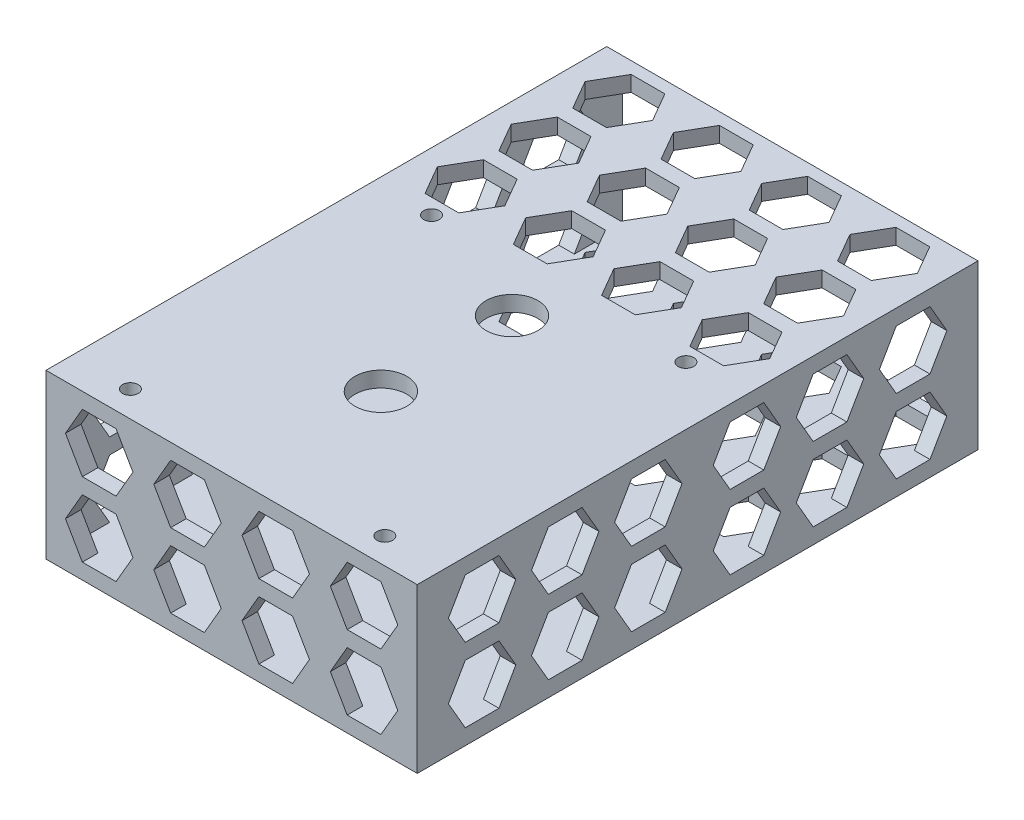
SolidWorks part; units mm, degrees
ref_plane "Front Plane" through (0, 0, 0) normal (0, 0, 1) x (1, 0, 0)
ref_plane "Top Plane" through (0, 0, 0) normal (0, 1, 0) x (1, 0, 0)
ref_plane "Right Plane" through (0, 0, 0) normal (1, 0, 0) x (0, 0, -1)
sketch "Sketch5" plane through (0, 0, 0) normal (0, 1, 0) x (1, 0, 0)
  line L1 (-35.75, -54) -> (35.75, -54)
  line L2 (-35.75, -54) -> (-35.75, 54)
  line L3 (-35.75, 54) -> (35.75, 54)
  line L4 (35.75, -54) -> (35.75, 54)
  line L5 (-35.75, -54) -> (35.75, 54) construction
  line L6 (-35.75, 54) -> (35.75, -54) construction
  point P0 (0, 0)
  dimension "D1" = 71.5
  dimension "D2" = 108
extrude "Boss-Extrude4" add sketch "Sketch5" along normal blind 31.5
shell "Shell1" thickness 3
sketch "Sketch7" plane through (0, 31.5, 0) normal (0, 1, 0) x (1, 0, 0)
  line L0 (-35.75, 0) -> (35.75, 0) construction
  line L1 (-35.75, 54) -> (-35.75, -54) construction
  line L2 (35.75, -54) -> (35.75, 54) construction
  circle A0 centre (0, 0) radius 1.75
  circle A2 centre (0, -25.25) radius 1.75
  dimension "D1" = 3.5
  dimension "D3" = 35.75
  dimension "D2" = 25.25
  dimension "D4" = 3.5
extrude "Cut-Extrude1" cut sketch "Sketch7" against normal through all
sketch "Sketch8" plane through (0, 31.5, 0) normal (0, 1, 0) x (1, 0, 0)
  circle A0 centre (0, -25.25) radius 5
  circle A1 centre (0, 0) radius 5
  circle A3 centre (0, 25.25) radius 5 [skipped]
  dimension "D1" = 10
  dimension "D3" = 25.25
  dimension "D2" = 3
extrude "Cut-Extrude2" cut sketch "Sketch8" against normal up to next
chamfer "Chamfer1" distance 1.5 angle 35 2 edges at (0, 3, 23.5) (0, 3, -1.75)
sketch "Sketch9" plane through (0, 31.5, 0) normal (0, 1, 0) x (1, 0, 0)
  line L0 (0, 54) -> (0, -54) construction
  line L1 (35.75, 54) -> (-35.75, 54) construction
  line L2 (-35.75, -54) -> (35.75, -54) construction
  circle A0 centre (-24.5, -49) radius 1.5
  circle A1 centre (24.5, -49) radius 1.5
  circle A2 centre (-24.5, 9) radius 1.5
  circle A3 centre (24.5, 9) radius 1.5
  dimension "D1" = 24.5
  dimension "D2" = 5
  dimension "D3" = 3
  dimension "D5" = 58
  dimension "D4" = 2
extrude "Cut-Extrude3" cut sketch "Sketch9" against normal up to next
sketch "Sketch10" plane through (0, 0, 54) normal (0, 0, 1) x (1, 0, 0)
  line L0 (-34, 28.5) -> (34, 28.5) construction
  line L1 (34, 28.5) -> (34, 3) construction
  line L2 (34, 3) -> (-34, 3) construction
  line L3 (-34, 3) -> (-34, 28.5) construction
  line L4 (-35.75, 31.5) -> (-35.75, 0) construction
  line L5 (-35.75, 31.5) -> (35.75, 31.5) construction
  line L6 (35.75, 31.5) -> (35.75, 0) construction
  line L7 (-35.75, 0) -> (35.75, 0) construction
  line L8 (-34, 15.75) -> (0, 15.75) construction
  line L9 (-32, 22.875) -> (-28.7524, 17.25)
  line L10 (-28.7524, 17.25) -> (-22.2572, 17.25)
  line L11 (-22.2572, 17.25) -> (-19.0096, 22.875)
  line L12 (-19.0096, 22.875) -> (-22.2572, 28.5)
  line L13 (-22.2572, 28.5) -> (-28.7524, 28.5)
  line L14 (-28.7524, 28.5) -> (-32, 22.875)
  line L15 (0, 28.5) -> (0, 3) construction
  line L16 (-28.7524, 3) -> (-32, 8.625)
  line L17 (-22.2572, 3) -> (-28.7524, 3)
  line L18 (-19.0096, 8.625) -> (-22.2572, 3)
  line L19 (-22.2572, 14.25) -> (-19.0096, 8.625)
  line L20 (-28.7524, 14.25) -> (-22.2572, 14.25)
  line L21 (-32, 8.625) -> (-28.7524, 14.25)
  line L22 (-17, 15.75) -> (-17, 28.5) construction
  line L23 (-11.7428, 3) -> (-5.2476, 3)
  line L24 (-14.9904, 8.625) -> (-11.7428, 3)
  line L25 (-11.7428, 14.25) -> (-14.9904, 8.625)
  line L26 (-5.2476, 14.25) -> (-11.7428, 14.25)
  line L27 (-2, 8.625) -> (-5.2476, 14.25)
  line L28 (-5.2476, 3) -> (-2, 8.625)
  line L29 (-5.2476, 28.5) -> (-2, 22.875)
  line L30 (-11.7428, 28.5) -> (-5.2476, 28.5)
  line L31 (-14.9904, 22.875) -> (-11.7428, 28.5)
  line L32 (-11.7428, 17.25) -> (-14.9904, 22.875)
  line L33 (-5.2476, 17.25) -> (-11.7428, 17.25)
  line L34 (-2, 22.875) -> (-5.2476, 17.25)
  line L35 (22.2572, 3) -> (28.7524, 3)
  line L36 (19.0096, 8.625) -> (22.2572, 3)
  line L37 (22.2572, 14.25) -> (19.0096, 8.625)
  line L38 (28.7524, 14.25) -> (22.2572, 14.25)
  line L39 (32, 8.625) -> (28.7524, 14.25)
  line L40 (28.7524, 3) -> (32, 8.625)
  line L41 (14.9904, 8.625) -> (11.7428, 3)
  line L42 (11.7428, 14.25) -> (14.9904, 8.625)
  line L43 (5.2476, 14.25) -> (11.7428, 14.25)
  line L44 (2, 8.625) -> (5.2476, 14.25)
  line L45 (5.2476, 3) -> (2, 8.625)
  line L46 (11.7428, 3) -> (5.2476, 3)
  line L47 (11.7428, 28.5) -> (5.2476, 28.5)
  line L48 (14.9904, 22.875) -> (11.7428, 28.5)
  line L49 (11.7428, 17.25) -> (14.9904, 22.875)
  line L50 (5.2476, 17.25) -> (11.7428, 17.25)
  line L51 (2, 22.875) -> (5.2476, 17.25)
  line L52 (5.2476, 28.5) -> (2, 22.875)
  line L53 (28.7524, 28.5) -> (32, 22.875)
  line L54 (22.2572, 28.5) -> (28.7524, 28.5)
  line L55 (19.0096, 22.875) -> (22.2572, 28.5)
  line L56 (22.2572, 17.25) -> (19.0096, 22.875)
  line L57 (28.7524, 17.25) -> (22.2572, 17.25)
  line L58 (32, 22.875) -> (28.7524, 17.25)
  circle A0 centre (-25.5048, 22.875) radius 5.625 construction
  dimension "D5" = 1.5
  dimension "D1" = 1.75
  dimension "D2" = 3
  dimension "D3" = 1.75
  dimension "D4" = 3
  dimension "D6" = 2
extrude "Cut-Extrude4" cut sketch "Sketch10" against normal up to next
sketch "Sketch12" plane through (-35.75, 0, 0) normal (-1, 0, 0) x (0, 0, 1)
  line L0 (51, 28.5) -> (-51, 28.5) construction
  line L1 (-51, 28.5) -> (-51, 3) construction
  line L2 (-51, 3) -> (51, 3) construction
  line L3 (51, 3) -> (51, 28.5) construction
  line L4 (-54, 31.5) -> (54, 31.5) construction
  line L5 (-54, 0) -> (54, 0) construction
  line L6 (-54, 31.5) -> (-54, 0) construction
  line L7 (54, 31.5) -> (54, 0) construction
  line L8 (0, 15.75) -> (51, 15.75) construction
  line L9 (0, 28.5) -> (0, 3) construction
  line L10 (25.5, 15.75) -> (25.5, 28.5) construction
  line L11 (48, 22.875) -> (44.7524, 28.5)
  line L12 (44.7524, 28.5) -> (38.2572, 28.5)
  line L13 (38.2572, 28.5) -> (35.0096, 22.875)
  line L14 (35.0096, 22.875) -> (38.2572, 17.25)
  line L15 (38.2572, 17.25) -> (44.7524, 17.25)
  line L16 (44.7524, 17.25) -> (48, 22.875)
  line L17 (6.2476, 17.25) -> (3, 22.875)
  line L18 (31.9952, 22.875) -> (28.7476, 28.5)
  line L19 (28.7476, 28.5) -> (22.2524, 28.5)
  line L20 (22.2524, 28.5) -> (19.0048, 22.875)
  line L21 (19.0048, 22.875) -> (22.2524, 17.25)
  line L22 (22.2524, 17.25) -> (28.7476, 17.25)
  line L23 (28.7476, 17.25) -> (31.9952, 22.875)
  line L24 (12.7428, 17.25) -> (6.2476, 17.25)
  line L25 (15.9904, 22.875) -> (12.7428, 17.25)
  line L26 (12.7428, 28.5) -> (15.9904, 22.875)
  line L27 (6.2476, 28.5) -> (12.7428, 28.5)
  line L28 (3, 22.875) -> (6.2476, 28.5)
  line L29 (44.7524, 14.25) -> (48, 8.625)
  line L30 (38.2572, 14.25) -> (44.7524, 14.25)
  line L31 (35.0096, 8.625) -> (38.2572, 14.25)
  line L32 (38.2572, 3) -> (35.0096, 8.625)
  line L33 (44.7524, 3) -> (38.2572, 3)
  line L34 (48, 8.625) -> (44.7524, 3)
  line L35 (28.7476, 14.25) -> (31.9952, 8.625)
  line L36 (22.2524, 14.25) -> (28.7476, 14.25)
  line L37 (19.0048, 8.625) -> (22.2524, 14.25)
  line L38 (22.2524, 3) -> (19.0048, 8.625)
  line L39 (28.7476, 3) -> (22.2524, 3)
  line L40 (31.9952, 8.625) -> (28.7476, 3)
  line L41 (12.7428, 14.25) -> (6.2476, 14.25)
  line L42 (15.9904, 8.625) -> (12.7428, 14.25)
  line L43 (12.7428, 3) -> (15.9904, 8.625)
  line L44 (6.2476, 3) -> (12.7428, 3)
  line L45 (3, 8.625) -> (6.2476, 3)
  line L46 (6.2476, 14.25) -> (3, 8.625)
  line L47 (-15.9904, 8.625) -> (-12.7428, 14.25)
  line L48 (-12.7428, 3) -> (-15.9904, 8.625)
  line L49 (-6.2476, 3) -> (-12.7428, 3)
  line L50 (-3, 8.625) -> (-6.2476, 3)
  line L51 (-6.2476, 14.25) -> (-3, 8.625)
  line L52 (-12.7428, 14.25) -> (-6.2476, 14.25)
  line L53 (-22.2524, 14.25) -> (-28.7476, 14.25)
  line L54 (-19.0048, 8.625) -> (-22.2524, 14.25)
  line L55 (-22.2524, 3) -> (-19.0048, 8.625)
  line L56 (-28.7476, 3) -> (-22.2524, 3)
  line L57 (-31.9952, 8.625) -> (-28.7476, 3)
  line L58 (-28.7476, 14.25) -> (-31.9952, 8.625)
  line L59 (-38.2572, 14.25) -> (-44.7524, 14.25)
  line L60 (-35.0096, 8.625) -> (-38.2572, 14.25)
  line L61 (-38.2572, 3) -> (-35.0096, 8.625)
  line L62 (-44.7524, 3) -> (-38.2572, 3)
  line L63 (-48, 8.625) -> (-44.7524, 3)
  line L64 (-44.7524, 14.25) -> (-48, 8.625)
  line L65 (-44.7524, 17.25) -> (-48, 22.875)
  line L66 (-38.2572, 17.25) -> (-44.7524, 17.25)
  line L67 (-35.0096, 22.875) -> (-38.2572, 17.25)
  line L68 (-38.2572, 28.5) -> (-35.0096, 22.875)
  line L69 (-44.7524, 28.5) -> (-38.2572, 28.5)
  line L70 (-48, 22.875) -> (-44.7524, 28.5)
  line L71 (-28.7476, 17.25) -> (-31.9952, 22.875)
  line L72 (-22.2524, 17.25) -> (-28.7476, 17.25)
  line L73 (-19.0048, 22.875) -> (-22.2524, 17.25)
  line L74 (-22.2524, 28.5) -> (-19.0048, 22.875)
  line L75 (-28.7476, 28.5) -> (-22.2524, 28.5)
  line L76 (-31.9952, 22.875) -> (-28.7476, 28.5)
  line L77 (-12.7428, 17.25) -> (-6.2476, 17.25)
  line L78 (-15.9904, 22.875) -> (-12.7428, 17.25)
  line L79 (-12.7428, 28.5) -> (-15.9904, 22.875)
  line L80 (-6.2476, 28.5) -> (-12.7428, 28.5)
  line L81 (-3, 22.875) -> (-6.2476, 28.5)
  line L82 (-6.2476, 17.25) -> (-3, 22.875)
  circle A0 centre (41.5048, 22.875) radius 5.625 construction
  circle A1 centre (25.5, 22.875) radius 5.625 construction
  dimension "D5" = 11.25
  dimension "D7" = 11.25
  dimension "D1" = 3
  dimension "D2" = 3
  dimension "D3" = 3
  dimension "D4" = 3
  dimension "D6" = 1.5
  dimension "D8" = 1.5
  dimension "D9" = 3
extrude "Cut-Extrude5" cut sketch "Sketch12" against normal through all
sketch "Sketch13" plane through (0, 31.5, 0) normal (0, 1, 0) x (1, 0, 0)
  line L0 (-34, 51.7) -> (34, 51.7) construction
  line L1 (34, 51.7) -> (34, 12) construction
  line L2 (34, 12) -> (-34, 12) construction
  line L3 (-34, 12) -> (-34, 51.7) construction
  line L5 (35.75, 54) -> (-35.75, 54) construction
  line L6 (-35.75, 54) -> (-35.75, -54) construction
  line L7 (35.75, -54) -> (35.75, 54) construction
  line L20 (0, 51.7) -> (0, 12) construction
  line L21 (0, 31.85) -> (-34, 31.85) construction
  line L22 (-17, 31.85) -> (-17, 12) construction
  line L23 (-22.2572, 51.7) -> (-19.0096, 46.075)
  line L24 (-19.0096, 31.85) -> (-22.2572, 37.475)
  line L25 (-22.2572, 37.475) -> (-28.7524, 37.475)
  line L26 (-28.7524, 37.475) -> (-32, 31.85)
  line L27 (-32, 31.85) -> (-28.7524, 26.225)
  line L28 (-28.7524, 26.225) -> (-22.2572, 26.225)
  line L29 (-22.2572, 26.225) -> (-19.0096, 31.85)
  line L30 (-19.0096, 17.625) -> (-22.2572, 23.25)
  line L31 (-22.2572, 23.25) -> (-28.7524, 23.25)
  line L32 (-28.7524, 23.25) -> (-32, 17.625)
  line L33 (-32, 17.625) -> (-28.7524, 12)
  line L34 (-28.7524, 12) -> (-22.2572, 12)
  line L35 (-22.2572, 12) -> (-19.0096, 17.625)
  line L36 (-28.7524, 51.7) -> (-22.2572, 51.7)
  line L37 (-32, 46.075) -> (-28.7524, 51.7)
  line L38 (-28.7524, 40.45) -> (-32, 46.075)
  line L39 (-22.2572, 40.45) -> (-28.7524, 40.45)
  line L40 (-19.0096, 46.075) -> (-22.2572, 40.45)
  line L41 (-5.2476, 51.7) -> (-11.7428, 51.7)
  line L42 (-2, 46.075) -> (-5.2476, 51.7)
  line L43 (-5.2476, 40.45) -> (-2, 46.075)
  line L44 (-11.7428, 40.45) -> (-5.2476, 40.45)
  line L45 (-14.9904, 46.075) -> (-11.7428, 40.45)
  line L46 (-11.7428, 51.7) -> (-14.9904, 46.075)
  line L47 (-11.7428, 26.225) -> (-14.9904, 31.85)
  line L48 (-5.2476, 26.225) -> (-11.7428, 26.225)
  line L49 (-2, 31.85) -> (-5.2476, 26.225)
  line L50 (-5.2476, 37.475) -> (-2, 31.85)
  line L51 (-11.7428, 37.475) -> (-5.2476, 37.475)
  line L52 (-14.9904, 31.85) -> (-11.7428, 37.475)
  line L53 (-11.7428, 12) -> (-14.9904, 17.625)
  line L54 (-5.2476, 12) -> (-11.7428, 12)
  line L55 (-2, 17.625) -> (-5.2476, 12)
  line L56 (-5.2476, 23.25) -> (-2, 17.625)
  line L57 (-11.7428, 23.25) -> (-5.2476, 23.25)
  line L58 (-14.9904, 17.625) -> (-11.7428, 23.25)
  line L59 (5.2476, 12) -> (11.7428, 12)
  line L60 (2, 17.625) -> (5.2476, 12)
  line L61 (5.2476, 23.25) -> (2, 17.625)
  line L62 (11.7428, 23.25) -> (5.2476, 23.25)
  line L63 (14.9904, 17.625) -> (11.7428, 23.25)
  line L64 (11.7428, 12) -> (14.9904, 17.625)
  line L65 (22.2572, 12) -> (19.0096, 17.625)
  line L66 (28.7524, 12) -> (22.2572, 12)
  line L67 (32, 17.625) -> (28.7524, 12)
  line L68 (28.7524, 23.25) -> (32, 17.625)
  line L69 (22.2572, 23.25) -> (28.7524, 23.25)
  line L70 (19.0096, 17.625) -> (22.2572, 23.25)
  line L71 (5.2476, 26.225) -> (11.7428, 26.225)
  line L72 (2, 31.85) -> (5.2476, 26.225)
  line L73 (5.2476, 37.475) -> (2, 31.85)
  line L74 (11.7428, 37.475) -> (5.2476, 37.475)
  line L75 (14.9904, 31.85) -> (11.7428, 37.475)
  line L76 (11.7428, 26.225) -> (14.9904, 31.85)
  line L77 (22.2572, 26.225) -> (19.0096, 31.85)
  line L78 (28.7524, 26.225) -> (22.2572, 26.225)
  line L79 (32, 31.85) -> (28.7524, 26.225)
  line L80 (28.7524, 37.475) -> (32, 31.85)
  line L81 (22.2572, 37.475) -> (28.7524, 37.475)
  line L82 (19.0096, 31.85) -> (22.2572, 37.475)
  line L83 (2, 46.075) -> (5.2476, 51.7)
  line L84 (5.2476, 40.45) -> (2, 46.075)
  line L85 (11.7428, 40.45) -> (5.2476, 40.45)
  line L86 (14.9904, 46.075) -> (11.7428, 40.45)
  line L87 (11.7428, 51.7) -> (14.9904, 46.075)
  line L88 (5.2476, 51.7) -> (11.7428, 51.7)
  line L89 (28.7524, 51.7) -> (22.2572, 51.7)
  line L90 (32, 46.075) -> (28.7524, 51.7)
  line L91 (28.7524, 40.45) -> (32, 46.075)
  line L92 (22.2572, 40.45) -> (28.7524, 40.45)
  line L93 (19.0096, 46.075) -> (22.2572, 40.45)
  line L94 (22.2572, 51.7) -> (19.0096, 46.075)
  circle A1 centre (-24.5, 9) radius 1.5 construction
  circle A2 centre (-25.5048, 31.85) radius 5.625 construction
  circle A3 centre (-25.5048, 17.625) radius 5.625 construction
  dimension "D2" = 3
  dimension "D5" = 11.25
  dimension "D8" = 11.25
  dimension "D1" = 2.3
  dimension "D3" = 1.75
  dimension "D4" = 1.75
  dimension "D6" = 2
  dimension "D7" = 5.625
  dimension "D9" = 0
  dimension "D10" = 2
extrude "Cut-Extrude6" cut sketch "Sketch13" against normal through all
